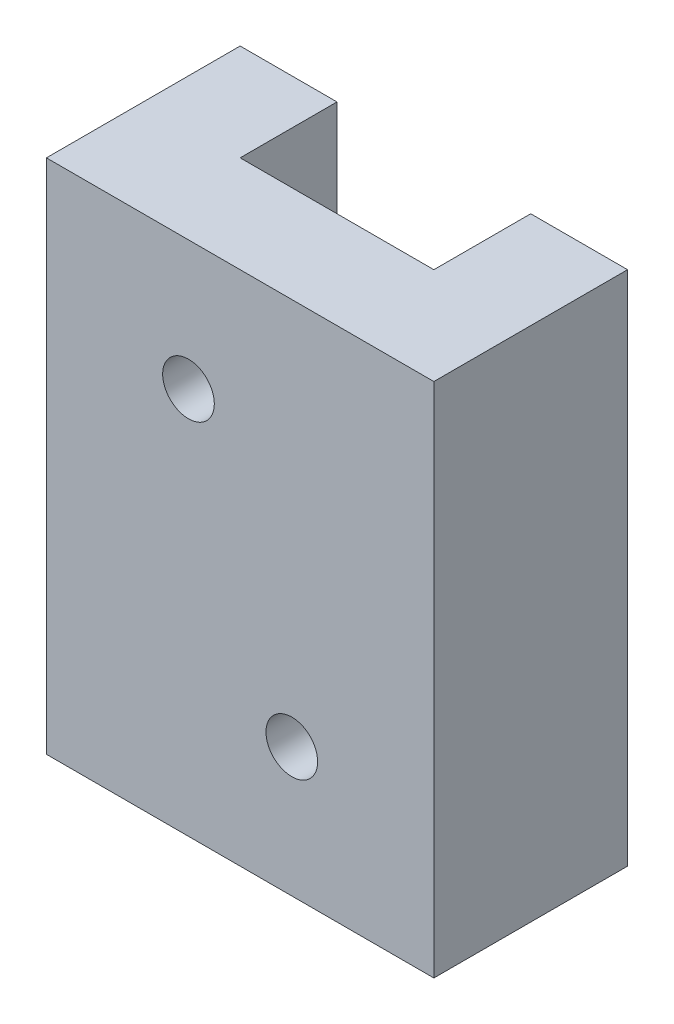
SolidWorks part; units mm, degrees
ref_plane "Plan de face" through (0, 0, 0) normal (0, 0, 1) x (1, 0, 0)
ref_plane "Plan de dessus" through (0, 0, 0) normal (0, 1, 0) x (1, 0, 0)
ref_plane "Plan de droite" through (0, 0, 0) normal (1, 0, 0) x (0, 0, -1)
sketch "Esquisse1" plane through (0, 0, 0) normal (0, 0, 1) x (1, 0, 0)
  line L0 (-7.5, 0) -> (7.5, 0)
  line L1 (-7.5, 0) -> (-7.5, 20)
  line L3 (7.5, 20) -> (7.5, 0)
  line L4 (0, 0) -> (2, 0)
  line L7 (-7.5, 20) -> (7.5, 20)
  circle A0 centre (2, 5) radius 1
  circle A1 centre (-2, 15) radius 1
  point P4 (0, 0)
extrude "Boss.-Extru.1" add sketch "Esquisse1" along normal blind 3.75 contours L7 L1 L0 L3 A1 A0
sketch "Esquisse2" plane through (0, 0, 0) normal (0, 0, -1) x (-1, 0, 0)
  line L0 (7.5, 20) -> (3.75, 20)
  line L1 (7.5, 20) -> (-7.5, 20) construction
  line L2 (3.75, 20) -> (3.75, 0)
  line L3 (7.5, 0) -> (-7.5, 0) construction
  line L4 (3.75, 0) -> (7.5, 0)
  line L5 (7.5, 0) -> (7.5, 20)
  line L6 (-7.5, 20) -> (-3.75, 20)
  line L7 (-3.75, 20) -> (-3.75, 0)
  line L8 (-3.75, 0) -> (-7.5, 0)
  line L9 (-7.5, 0) -> (-7.5, 20)
extrude "Boss.-Extru.2" add sketch "Esquisse2" along normal blind 3.75
